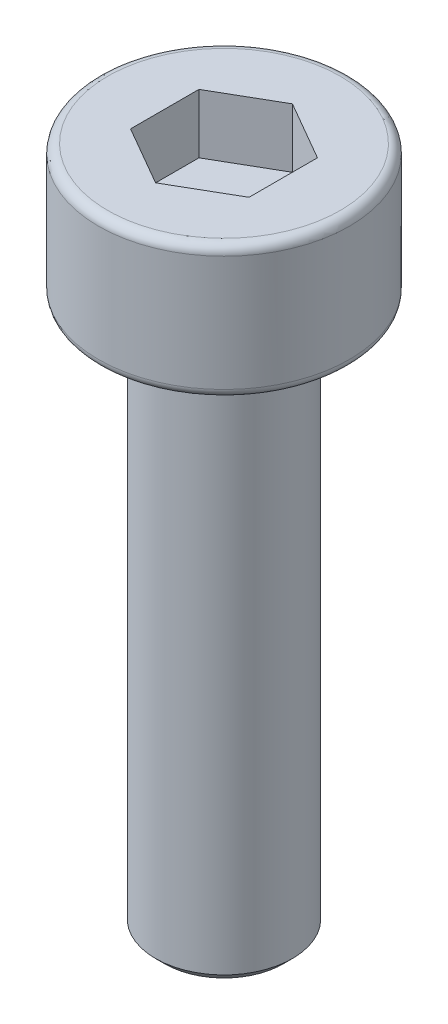
SolidWorks part; units mm, degrees
material "普通碳钢"
ref_plane "前视基准面" through (0, 0, 0) normal (0, 0, 1) x (1, 0, 0)
ref_plane "上视基准面" through (0, 0, 0) normal (0, 1, 0) x (1, 0, 0)
ref_plane "右视基准面" through (0, 0, 0) normal (1, 0, 0) x (0, 0, -1)
sketch "草图1" plane through (0, 0, 0) normal (0, 0, 1) x (1, 0, 0)
  line L0 (0, 0) -> (0, -21.235) construction
  line L1 (0, 0) -> (2.75, 0)
  line L2 (2.75, 0) -> (2.75, -2.93)
  line L3 (2.75, -2.93) -> (1.5, -2.93)
  line L4 (1.5, -2.93) -> (1.5, -14.93)
  line L5 (1.5, -14.93) -> (0, -14.93)
  line L6 (0, -14.93) -> (0, 0)
  point P5 (2.125, -2.93)
  dimension "D1" = 2.93
  dimension "D2" = 5.5
  dimension "D3" = 3
  dimension "D4" = 12
revolve "旋转1" add sketch "草图1" angle 360 about L0
cosmetic thread "装饰螺纹线1" parameters "D2"=2.459
sketch "草图2" plane through (0, 0, 0) normal (0, 1, 0) x (1, 0, 0)
  line L1 (0, 1.5) -> (-1.299, 0.75)
  line L2 (-1.299, 0.75) -> (-1.299, -0.75)
  line L3 (-1.299, -0.75) -> (0, -1.5)
  line L4 (0, -1.5) -> (1.299, -0.75)
  line L5 (1.299, -0.75) -> (1.299, 0.75)
  line L6 (1.299, 0.75) -> (0, 1.5)
  circle A0 centre (0, 0) radius 1.5 construction
  dimension "D1" = 3
extrude "切除-拉伸1" cut sketch "草图2" against normal blind 1.3
fillet "圆角1" radius 0.2 2 edges at (0, 0, 2.75) (0, -2.93, 2.75)
chamfer "倒角1" distance 0.2 angle 45 1 edges at (0, -14.93, 1.5)
